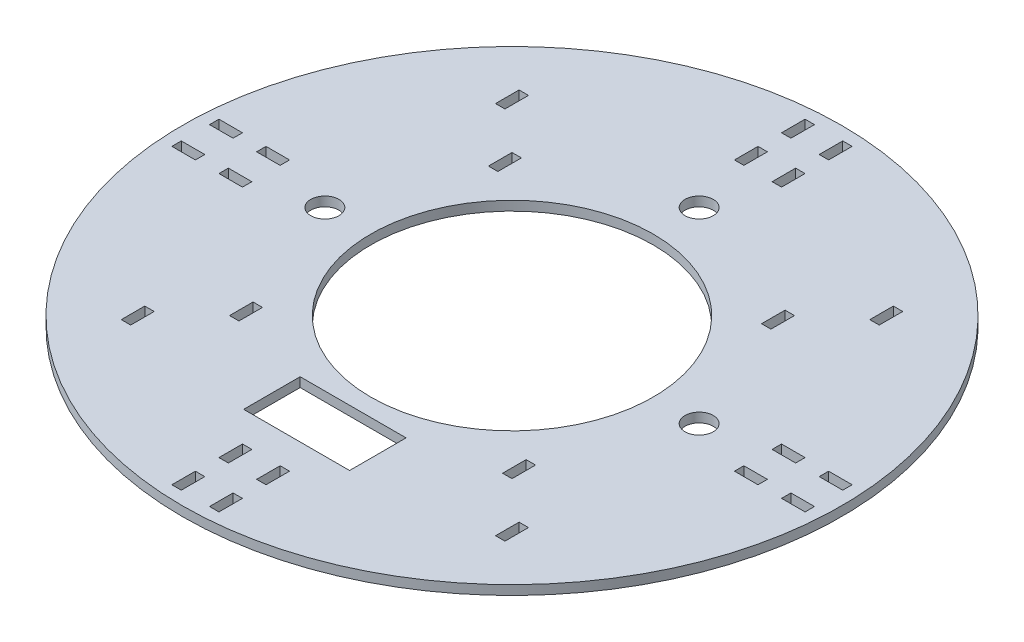
SolidWorks part; units mm, degrees
ref_plane "Front Plane" through (0, 0, 0) normal (0, 0, 1) x (1, 0, 0)
ref_plane "Top Plane" through (0, 0, 0) normal (0, 1, 0) x (1, 0, 0)
ref_plane "Right Plane" through (0, 0, 0) normal (1, 0, 0) x (0, 0, -1)
sketch "Sketch1" plane through (0, 0, 0) normal (0, 1, 0) x (1, 0, 0)
  line L0 (-49.4975, 49.4975) -> (-30, 30) construction
  line L1 (-52.2487, 5) -> (-67.2487, 5) construction
  line L2 (-67.2487, 5) -> (-67.2487, -5) construction
  line L3 (-67.2487, -5) -> (-52.2487, -5) construction
  line L4 (-52.2487, -5) -> (-52.2487, 5) construction
  line L5 (-30, -30) -> (30, 30) construction
  line L6 (-30, 30) -> (30, -30) construction
  line L7 (-30, 30) -> (-28, 30)
  line L8 (-30, 30) -> (-30, 25)
  line L9 (-30, 25) -> (-28, 25)
  line L10 (-28, 30) -> (-28, 25)
  line L11 (30, 30) -> (28, 30)
  line L12 (30, 30) -> (30, 25)
  line L13 (30, 25) -> (28, 25)
  line L14 (28, 30) -> (28, 25)
  line L15 (-30, -30) -> (-28, -30)
  line L16 (-30, -30) -> (-30, -25)
  line L17 (-30, -25) -> (-28, -25)
  line L18 (-28, -30) -> (-28, -25)
  line L19 (30, -30) -> (28, -30)
  line L20 (30, -30) -> (30, -25)
  line L21 (30, -25) -> (28, -25)
  line L22 (28, -30) -> (28, -25)
  line L23 (30, 30) -> (49.4975, 49.4975) construction
  line L24 (-49.4975, -49.4975) -> (-30, -30) construction
  line L25 (-30, -30) -> (-30, 30) construction
  line L26 (-30, 30) -> (30, 30) construction
  line L27 (30, 30) -> (30, -30) construction
  line L28 (30, -30) -> (30.057, -29.7836) construction
  line L29 (49.4975, -49.4975) -> (30, -30) construction
  line L30 (0, 49.4975) -> (0, 70) construction
  line L31 (-40.7487, 42.2487) -> (-38.7487, 42.2487)
  line L32 (-40.7487, 42.2487) -> (-40.7487, 37.2487)
  line L33 (-40.7487, 37.2487) -> (-38.7487, 37.2487)
  line L34 (-38.7487, 42.2487) -> (-38.7487, 37.2487)
  line L35 (-40.7487, 42.2487) -> (-38.7487, 37.2487) construction
  line L36 (-40.7487, 37.2487) -> (-38.7487, 42.2487) construction
  line L37 (38.7487, 42.2487) -> (40.7487, 42.2487)
  line L38 (38.7487, 42.2487) -> (38.7487, 37.2487)
  line L39 (38.7487, 37.2487) -> (40.7487, 37.2487)
  line L40 (40.7487, 42.2487) -> (40.7487, 37.2487)
  line L41 (38.7487, 42.2487) -> (40.7487, 37.2487) construction
  line L42 (38.7487, 37.2487) -> (40.7487, 42.2487) construction
  line L43 (38.7487, -37.2487) -> (40.7487, -37.2487)
  line L44 (38.7487, -37.2487) -> (38.7487, -42.2487)
  line L45 (38.7487, -42.2487) -> (40.7487, -42.2487)
  line L46 (40.7487, -37.2487) -> (40.7487, -42.2487)
  line L47 (38.7487, -37.2487) -> (40.7487, -42.2487) construction
  line L48 (38.7487, -42.2487) -> (40.7487, -37.2487) construction
  line L49 (-40.7487, -37.2487) -> (-38.7487, -37.2487)
  line L50 (-40.7487, -37.2487) -> (-40.7487, -42.2487)
  line L51 (-40.7487, -42.2487) -> (-38.7487, -42.2487)
  line L52 (-38.7487, -37.2487) -> (-38.7487, -42.2487)
  line L53 (-40.7487, -37.2487) -> (-38.7487, -42.2487) construction
  line L54 (-40.7487, -42.2487) -> (-38.7487, -37.2487) construction
  line L55 (-49.4975, 0) -> (-70, 0) construction
  line L56 (49.4975, 0) -> (70, 0) construction
  line L57 (0, -49.4975) -> (0, -70) construction
  line L58 (-49.4975, 0) -> (-30, 0) construction
  line L60 (-11.25, -33.7487) -> (11.25, -33.7487)
  line L61 (-11.25, -33.7487) -> (-11.25, -45.7487)
  line L62 (-11.25, -45.7487) -> (11.25, -45.7487)
  line L63 (-5, 52.2487) -> (5, 67.2487) construction
  line L64 (-5, 67.2487) -> (5, 52.2487) construction
  line L65 (-5, 52.2487) -> (5, 52.2487) construction
  line L66 (5, 52.2487) -> (5, 67.2487) construction
  line L67 (5, 67.2487) -> (-5, 67.2487) construction
  line L68 (-5, 67.2487) -> (-5, 52.2487) construction
  line L69 (52.2487, -5) -> (67.2487, 5) construction
  line L70 (52.2487, 5) -> (67.2487, -5) construction
  line L71 (52.2487, -5) -> (67.2487, -5) construction
  line L72 (67.2487, -5) -> (67.2487, 5) construction
  line L73 (67.2487, 5) -> (52.2487, 5) construction
  line L74 (52.2487, 5) -> (52.2487, -5) construction
  line L75 (-5, -52.2487) -> (5, -67.2487) construction
  line L76 (-5, -67.2487) -> (5, -52.2487) construction
  line L77 (-5, -52.2487) -> (5, -52.2487) construction
  line L78 (5, -52.2487) -> (5, -67.2487) construction
  line L79 (5, -67.2487) -> (-5, -67.2487) construction
  line L80 (-5, -67.2487) -> (-5, -52.2487) construction
  line L81 (-67.2487, 5) -> (-52.2487, -5) construction
  line L82 (-67.2487, -5) -> (-52.2487, 5) construction
  line L83 (-67.2487, 5) -> (-62.2487, 5)
  line L84 (-67.2487, 5) -> (-67.2487, 3)
  line L85 (-67.2487, 3) -> (-62.2487, 3)
  line L86 (-62.2487, 5) -> (-62.2487, 3)
  line L87 (-67.2487, -5) -> (-62.2487, -5)
  line L88 (-67.2487, -5) -> (-67.2487, -3)
  line L89 (-67.2487, -3) -> (-62.2487, -3)
  line L90 (-62.2487, -5) -> (-62.2487, -3)
  line L91 (-52.2487, -5) -> (-57.2487, -5)
  line L92 (-52.2487, -5) -> (-52.2487, -3)
  line L93 (-52.2487, -3) -> (-57.2487, -3)
  line L94 (-57.2487, -5) -> (-57.2487, -3)
  line L95 (-52.2487, 5) -> (-57.2487, 5)
  line L96 (-52.2487, 5) -> (-52.2487, 3)
  line L97 (-52.2487, 3) -> (-57.2487, 3)
  line L98 (-57.2487, 5) -> (-57.2487, 3)
  line L99 (-5, 67.2487) -> (-3, 67.2487)
  line L100 (-5, 67.2487) -> (-5, 62.2487)
  line L101 (-5, 62.2487) -> (-3, 62.2487)
  line L102 (-3, 67.2487) -> (-3, 62.2487)
  line L103 (-5, 52.2487) -> (-3, 52.2487)
  line L104 (-5, 52.2487) -> (-5, 57.2487)
  line L105 (-5, 57.2487) -> (-3, 57.2487)
  line L106 (-3, 52.2487) -> (-3, 57.2487)
  line L107 (5, 52.2487) -> (3, 52.2487)
  line L108 (5, 52.2487) -> (5, 57.2487)
  line L109 (5, 57.2487) -> (3, 57.2487)
  line L110 (3, 52.2487) -> (3, 57.2487)
  line L111 (5, 67.2487) -> (3, 67.2487)
  line L112 (5, 67.2487) -> (5, 62.2487)
  line L113 (5, 62.2487) -> (3, 62.2487)
  line L114 (3, 67.2487) -> (3, 62.2487)
  line L115 (52.2487, 5) -> (57.2487, 5)
  line L116 (52.2487, 5) -> (52.2487, 3)
  line L117 (52.2487, 3) -> (57.2487, 3)
  line L118 (57.2487, 5) -> (57.2487, 3)
  line L119 (52.2487, -5) -> (57.2487, -5)
  line L120 (52.2487, -5) -> (52.2487, -3)
  line L121 (52.2487, -3) -> (57.2487, -3)
  line L122 (57.2487, -5) -> (57.2487, -3)
  line L123 (67.2487, 5) -> (62.2487, 5)
  line L124 (67.2487, 5) -> (67.2487, 3)
  line L125 (67.2487, 3) -> (62.2487, 3)
  line L126 (62.2487, 5) -> (62.2487, 3)
  line L127 (67.2487, -5) -> (62.2487, -5)
  line L128 (67.2487, -5) -> (67.2487, -3)
  line L129 (67.2487, -3) -> (62.2487, -3)
  line L130 (62.2487, -5) -> (62.2487, -3)
  line L131 (-5, -52.2487) -> (-3, -52.2487)
  line L132 (-5, -52.2487) -> (-5, -57.2487)
  line L133 (-5, -57.2487) -> (-3, -57.2487)
  line L134 (-3, -52.2487) -> (-3, -57.2487)
  line L135 (5, -52.2487) -> (3, -52.2487)
  line L136 (5, -52.2487) -> (5, -57.2487)
  line L137 (5, -57.2487) -> (3, -57.2487)
  line L138 (3, -52.2487) -> (3, -57.2487)
  line L139 (5, -67.2487) -> (3, -67.2487)
  line L140 (5, -67.2487) -> (5, -62.2487)
  line L141 (5, -62.2487) -> (3, -62.2487)
  line L142 (3, -67.2487) -> (3, -62.2487)
  line L143 (-5, -67.2487) -> (-3, -67.2487)
  line L144 (-5, -67.2487) -> (-5, -62.2487)
  line L145 (-5, -62.2487) -> (-3, -62.2487)
  line L146 (-3, -67.2487) -> (-3, -62.2487)
  line L147 (0, 49.4975) -> (0, 30) construction
  line L148 (30, 0) -> (49.4975, 0) construction
  line L149 (0, -30) -> (0, -49.4975) construction
  line L150 (-49.4975, -49.4975) -> (-49.4975, 49.4975) construction
  line L151 (-49.4975, 49.4975) -> (49.4975, 49.4975) construction
  line L152 (49.4975, 49.4975) -> (49.4975, -49.4975) construction
  line L153 (49.4975, -49.4975) -> (-49.4975, -49.4975) construction
  line L154 (-30, -30) -> (30, -30) construction
  line L155 (-52.2487, 5) -> (-67.2487, 5) construction
  line L156 (11.25, -33.7487) -> (11.25, -45.7487)
  line L157 (-11.25, -33.7487) -> (11.25, -45.7487) construction
  line L158 (-11.25, -45.7487) -> (11.25, -33.7487) construction
  circle A0 centre (0, 0) radius 30
  circle A1 centre (0, 0) radius 70
  circle A2 centre (0, -39.7487) radius 3
  circle A3 centre (39.7487, 0) radius 3
  circle A4 centre (-39.7487, 0) radius 3
  circle A5 centre (0, 39.7487) radius 3
  point P20 (-39.7487, 39.7487)
  point P29 (39.7487, 39.7487)
  point P34 (39.7487, -39.7487)
  point P39 (-39.7487, -39.7487)
  point P52 (0, 59.7487)
  point P57 (59.7487, 0)
  point P62 (0, -59.7487)
  point P67 (-59.7487, 0)
  dimension "D1" = 60
  dimension "D2" = 140
  dimension "D65" = 6
  dimension "D66" = 6
  dimension "D67" = 6
  dimension "D68" = 6
  dimension "D3" = 60
  dimension "D4" = 60
  dimension "D5" = 5
  dimension "D6" = 2
  dimension "D7" = 5
  dimension "D8" = 2
  dimension "D9" = 2
  dimension "D10" = 5
  dimension "D11" = 2
  dimension "D12" = 5
  dimension "D13" = 5
  dimension "D14" = 2
  dimension "D15" = 5
  dimension "D16" = 2
  dimension "D17" = 2
  dimension "D18" = 5
  dimension "D19" = 2
  dimension "D20" = 5
  dimension "D21" = 20.5025
  dimension "D22" = 15
  dimension "D23" = 10
  dimension "D24" = 20.5025
  dimension "D25" = 15
  dimension "D26" = 10
  dimension "D27" = 20.5025
  dimension "D28" = 15
  dimension "D29" = 10
  dimension "D30" = 20.5025
  dimension "D31" = 15
  dimension "D32" = 10
  dimension "D33" = 5
  dimension "D34" = 2
  dimension "D35" = 5
  dimension "D36" = 2
  dimension "D37" = 5
  dimension "D38" = 2
  dimension "D39" = 5
  dimension "D40" = 5
  dimension "D41" = 5
  dimension "D42" = 5
  dimension "D43" = 5
  dimension "D44" = 2
  dimension "D45" = 2
  dimension "D46" = 2
  dimension "D47" = 2
  dimension "D48" = 5
  dimension "D49" = 5
  dimension "D50" = 5
  dimension "D51" = 5
  dimension "D52" = 2
  dimension "D53" = 2
  dimension "D54" = 2
  dimension "D55" = 2
  dimension "D56" = 2
  dimension "D57" = 5
  dimension "D58" = 5
  dimension "D59" = 2
  dimension "D60" = 2
  dimension "D61" = 2
  dimension "D62" = 5
  dimension "D63" = 5
  dimension "D64" = 2
  dimension "D69" = 19.4975
  dimension "D70" = 22.5
  dimension "D71" = 12
extrude "Yükseklik-Ekstrüzyon1" add sketch "Sketch1" along normal blind 2 contours A1 A5 A4 A3 L60 L156 L62 L61 L146 L143 L144 L145 L131 L134 L133 L132 L115 L118 L117 L116 L114 L111 L112 L113 L99 L102 L101 L100 L98 L95 L96 L97 L83 L86 L85 L84 L43 L46 L45
sketch "Sketch2" plane through (0, 2, 0) normal (0, 1, 0) x (1, 0, 0)
  line L0 (-52.2487, 5) -> (-52.2487, 21.5478)
  line L1 (-52.2487, 21.5478) -> (-52.2487, -8.4522)
  dimension "D1" = 30
